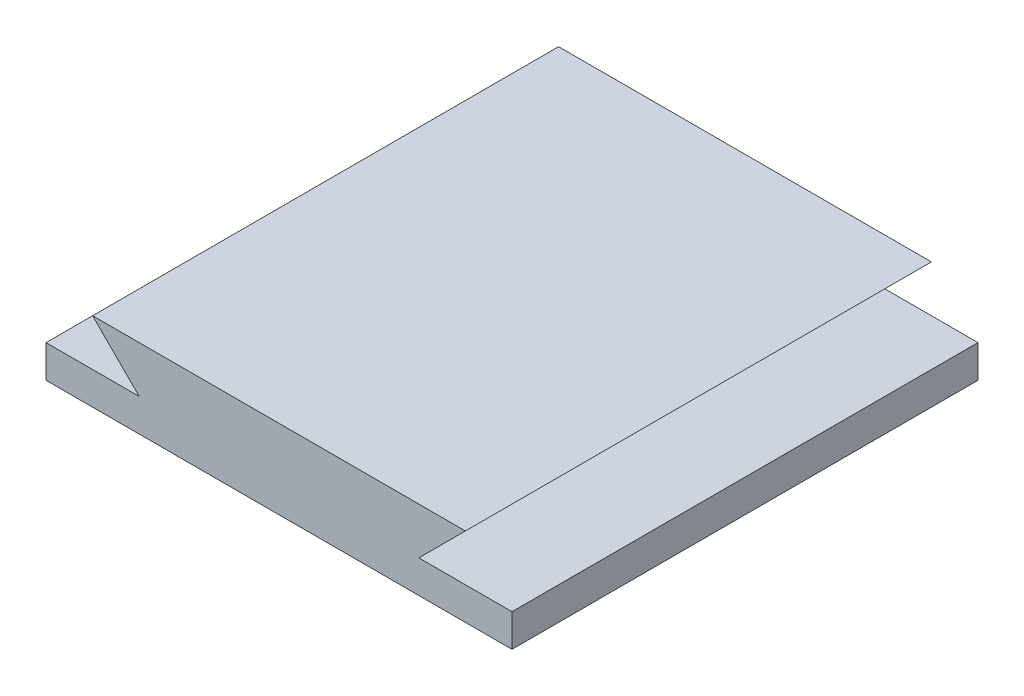
SolidWorks part; units mm, degrees
material "Aleación 1060"
ref_plane "Alzado" through (0, 0, 0) normal (0, 0, 1) x (1, 0, 0)
ref_plane "Planta" through (0, 0, 0) normal (0, 1, 0) x (1, 0, 0)
ref_plane "Vista lateral" through (0, 0, 0) normal (1, 0, 0) x (0, 0, -1)
sketch "Croquis1" plane through (0, 0, 0) normal (0, 0, 1) x (1, 0, 0)
  line L0 (-30, 3.5) -> (-40, 13.5)
  line L1 (50, -3.5) -> (-50, -3.5)
  line L2 (50, -3.5) -> (50, 3.5)
  line L3 (50, 3.5) -> (-50, 3.5)
  line L4 (-50, -3.5) -> (-50, 3.5)
  line L5 (50, -3.5) -> (-50, 3.5) construction
  line L6 (50, 3.5) -> (-50, -3.5) construction
  line L7 (-40, 13.5) -> (40, 13.5)
  line L8 (40, 13.5) -> (30, 3.5)
  line L9 (30, 3.5) -> (-30, 3.5)
  point P0 (0, 0)
  dimension "D1" = 100
  dimension "D2" = 7
  dimension "D3" = 45
  dimension "D4" = 20
  dimension "D5" = 20
  dimension "D6" = 10
extrude "Saliente-Extruir1" add sketch "Croquis1" along normal blind 100 contours L8 L7 L0 L3 | L4 L1 L2 L3
